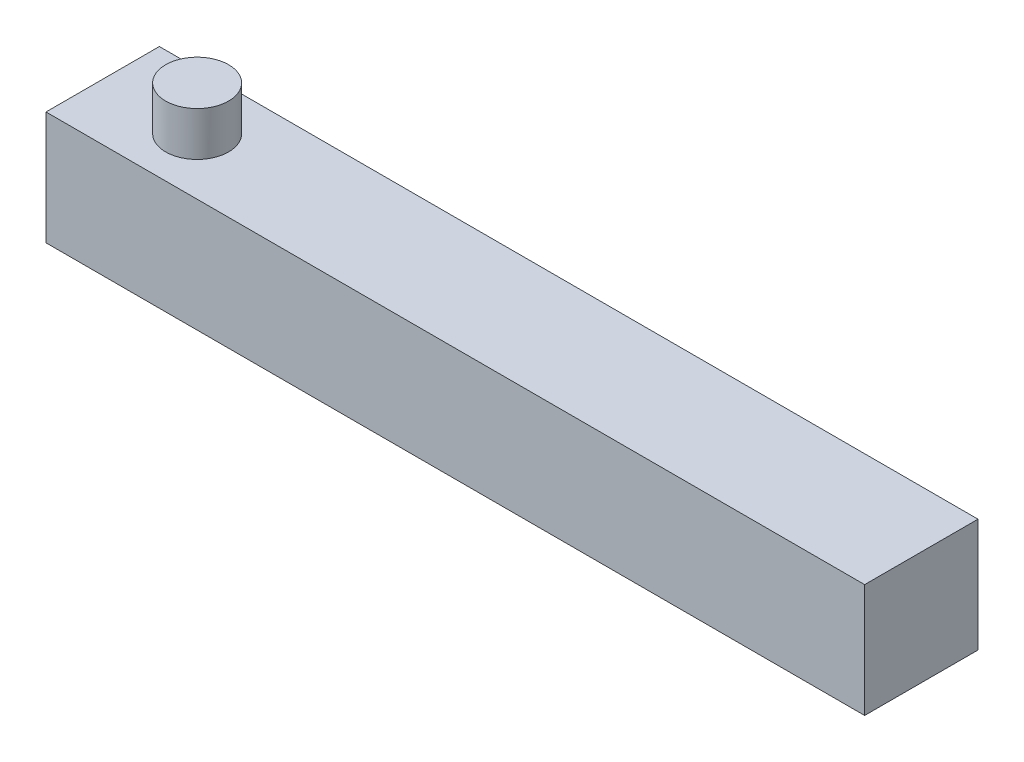
SolidWorks part; units mm, degrees
ref_plane "前基準面" through (0, 0, 0) normal (0, 0, 1) x (1, 0, 0)
ref_plane "上基準面" through (0, 0, 0) normal (0, 1, 0) x (1, 0, 0)
ref_plane "右基準面" through (0, 0, 0) normal (1, 0, 0) x (0, 0, -1)
sketch "草圖1" plane through (0, 0, 0) normal (0, 1, 0) x (1, 0, 0)
  line L1 (-32.5, -4.5) -> (32.5, -4.5)
  line L2 (-32.5, -4.5) -> (-32.5, 4.5)
  line L3 (-32.5, 4.5) -> (32.5, 4.5)
  line L4 (32.5, -4.5) -> (32.5, 4.5)
  line L5 (-32.5, -4.5) -> (32.5, 4.5) construction
  line L6 (-32.5, 4.5) -> (32.5, -4.5) construction
  point P0 (0, 0)
  dimension "D1" = 65
  dimension "D2" = 9
extrude "填料-伸長1" add sketch "草圖1" along normal blind 9
sketch "草圖2" plane through (0, 9, 0) normal (0, 1, 0) x (1, 0, 0)
  line L0 (-25, 0) -> (25, 0)
  line L1 (-32.5, -4.5) -> (32.5, -4.5) construction
  line L2 (32.5, -4.5) -> (32.5, 4.5) construction
  circle A0 centre (-25, 0) radius 2.5
  dimension "D5" = 5
  dimension "D1" = 4.5
  dimension "D2" = 50
  dimension "D3" = 7.5
extrude "填料-伸長2" add sketch "草圖2" along normal blind 3.5
